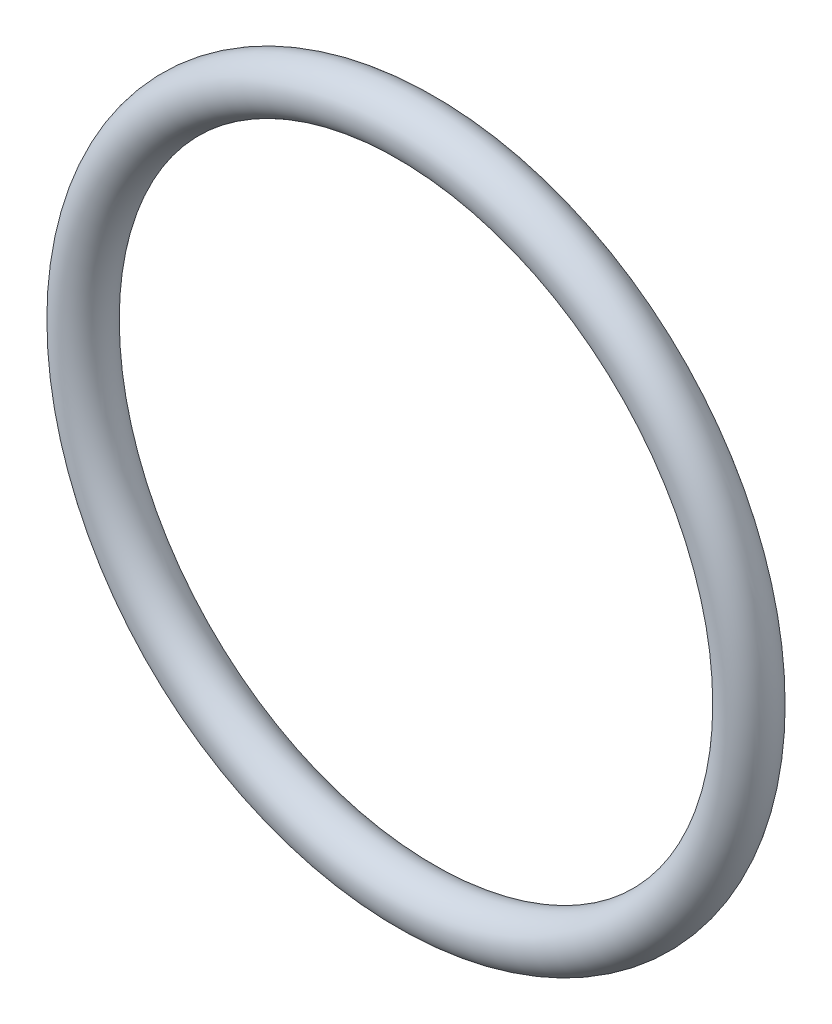
SolidWorks part; units mm, degrees
ref_plane "Front Plane" through (0, 0, 0) normal (0, 0, 1) x (1, 0, 0)
ref_plane "Top Plane" through (0, 0, 0) normal (0, 1, 0) x (1, 0, 0)
ref_plane "Right Plane" through (0, 0, 0) normal (1, 0, 0) x (0, 0, -1)
sketch "Sketch2" plane through (0, 0, 0) normal (0, 1, 0) x (1, 0, 0)
  line L0 (0, 11.7965) -> (0, -11.7965) construction
  line L1 (-10.3187, 0) -> (0, 0) construction
  circle A0 centre (-10.3187, 0) radius 0.7937
  point P4 (0, 0)
  dimension "D2" = 1.5875
  dimension "D1" = 10.3187
revolve "Revolve1" add sketch "Sketch2" angle 360 about L0
